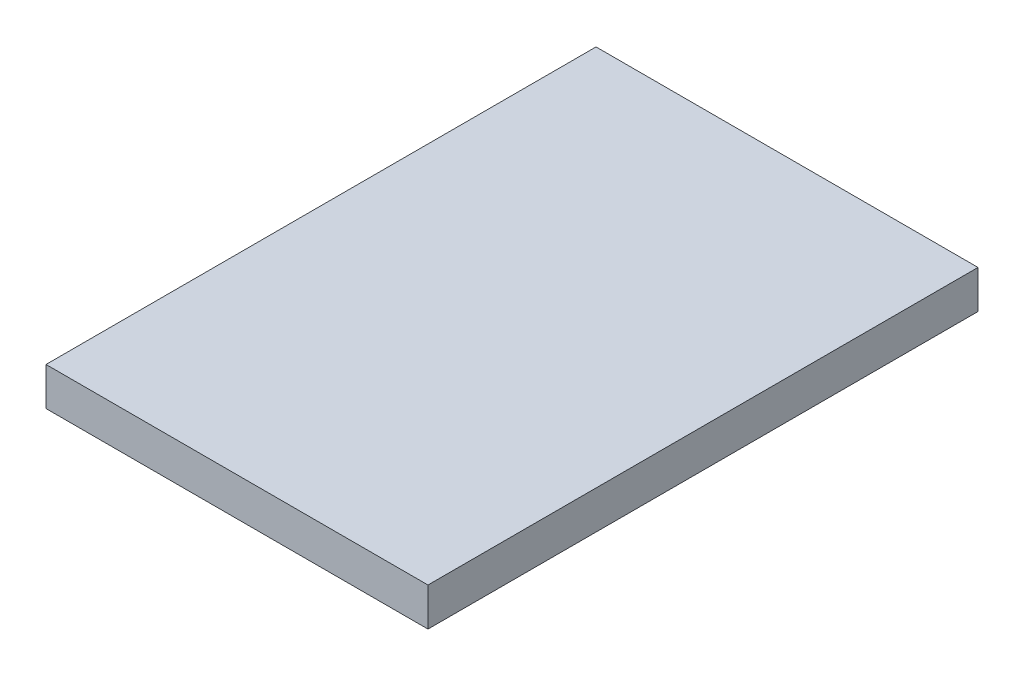
SolidWorks part; units mm, degrees
ref_plane "Front Plane" through (0, 0, 0) normal (0, 0, 1) x (1, 0, 0)
ref_plane "Top Plane" through (0, 0, 0) normal (0, 1, 0) x (1, 0, 0)
ref_plane "Right Plane" through (0, 0, 0) normal (1, 0, 0) x (0, 0, -1)
sketch "Sketch1" plane through (0, 0, 0) normal (0, 1, 0) x (1, 0, 0)
  line L1 (-12.5, -18) -> (12.5, -18)
  line L2 (-12.5, -18) -> (-12.5, 18)
  line L3 (-12.5, 18) -> (12.5, 18)
  line L4 (12.5, -18) -> (12.5, 18)
  line L5 (-12.5, -18) -> (12.5, 18) construction
  line L6 (-12.5, 18) -> (12.5, -18) construction
  point P0 (0, 0)
  dimension "D1" = 25
  dimension "D2" = 36
extrude "Boss-Extrude1" add sketch "Sketch1" along normal blind 2.5
